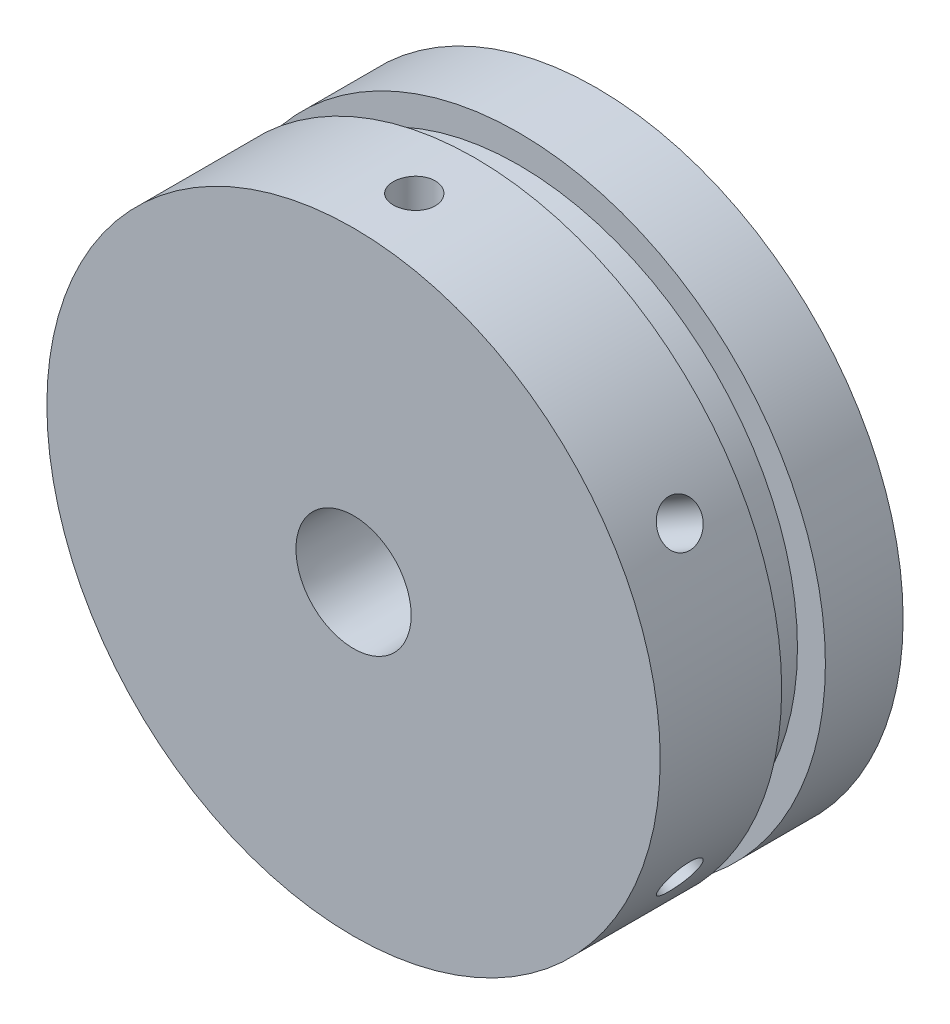
SolidWorks part; units mm, degrees
material "6061-T6 (SS)"
ref_plane "Front Plane" through (0, 0, 0) normal (0, 0, 1) x (1, 0, 0)
ref_plane "Top Plane" through (0, 0, 0) normal (0, 1, 0) x (1, 0, 0)
ref_plane "Right Plane" through (0, 0, 0) normal (1, 0, 0) x (0, 0, -1)
sketch "Sketch2" plane through (0, 0, 0) normal (0, 0, 1) x (1, 0, 0)
  circle A0 centre (0, 0) radius 25.25
  dimension "D1" = 50.5
extrude "Boss-Extrude1" add sketch "Sketch2" along normal blind 20
sketch "Sketch3" plane through (0, 0, 0) normal (1, 0, 0) x (0, 0, -1)
  line L0 (0, 25.25) -> (-20, 25.25) construction
  line L1 (-10, 25.25) -> (-6.4, 25.25)
  line L2 (-10, 25.25) -> (-10, 22.95)
  line L3 (-10, 22.95) -> (-6.4, 22.95)
  line L4 (-6.4, 25.25) -> (-6.4, 22.95)
  line L5 (0, 0) -> (-20.027, 0) construction
  dimension "D1" = 2.3
  dimension "D2" = 3.6
  dimension "D3" = 10
revolve "Cut-Revolve1" cut sketch "Sketch3" angle 360 about L5
ref_plane "Plane1" through (0, 25.25, 0) normal (0, 1, 0) x (1, 0, 0)
sketch "Sketch4" plane through (0, 25.25, 0) normal (0, 1, 0) x (1, 0, 0)
  line L0 (0, 0) -> (0, -20.5452) construction
hole_wizard "#8-32 Tapped Hole2" positions "3DSketch3" profile "Sketch7" tap size "#8-32" standard "ANSI Inch"
sketch3d "3DSketch3"
  line L0 (0, 25.25, 0) -> (0, 25.25, 20.5452) construction
  circle A1 centre (0, 0, 20) radius 25.25 construction
  point P0 (0, 25.25, 15)
  point P8 (0, 25.25, 20)
  point P12 (0, 0, 45.25)
  dimension "D1" = 5
sketch "Sketch7" plane through (0, 25.25, 15) normal (1, 0, 0) x (0, 0, 1)
  line L0 (0, 0) -> (0, 11.0378)
  line L1 (0, 11.0378) -> (1.7272, 10)
  line L2 (1.7272, 10) -> (1.7272, 0)
  line L5 (1.7272, 0) -> (0, 0)
  line L10 (0, 11.0378) -> (-1.7272, 10) construction
  line L11 (0, -6.35) -> (0, 107.95) construction
  dimension "Tap Drill Dia." = 3.4544
  dimension "Tap Drill Depth" = 10
  dimension "Drill Angle" = 118
cosmetic thread "Hole Thread5" parameters "D1"=8.33, "D2"=4.1656
sketch "Sketch9" plane through (0, 0, 0) normal (1, 0, 0) x (0, 0, -1)
  line L0 (-21.7688, 0) -> (0, 0) construction
pattern_circular "CirPattern1" count 6 over 360 about axis through (0, 0, 21.7688) along (0, 0, -1) of "#8-32 Tapped Hole2"
cosmetic thread "Hole Thread6" parameters "D1"=8.33, "D2"=4.1656
cosmetic thread "Hole Thread7" parameters "D1"=8.33, "D2"=4.1656
cosmetic thread "Hole Thread8" parameters "D1"=8.33, "D2"=4.1656
cosmetic thread "Hole Thread9" parameters "D1"=8.33, "D2"=4.1656
cosmetic thread "Hole Thread10" parameters "D1"=8.33, "D2"=4.1656
hole_wizard "1/8 NPT Tapped Hole1" positions "Sketch10" profile "Sketch11" size "1/8" standard "ANSI Inch"
sketch "Sketch10" plane through (0, 0, 20) normal (0, 0, 1) x (1, 0, 0)
  line L1 (-6.35, 0) -> (6.35, 0) construction
  point P0 (0, 0)
cosmetic thread "Hole Thread11" parameters "D1"=6.92, "D2"=10.2867
sketch "Sketch11" plane through (0, 0, 20) normal (1, 0, 0) x (0, -1, 0)
  line L0 (0, 0) -> (0, 17.5335)
  line L1 (4.2164, 15) -> (0, 17.5335)
  line L2 (-4.2164, 15) -> (0, 17.5335) construction
  line L3 (4.2164, 15) -> (4.2164, 6.92)
  line L4 (4.2164, 6.92) -> (4.5286, 6.92)
  line L5 (4.5286, 6.92) -> (4.7446, 0)
  line L6 (-4.5286, 6.92) -> (-4.7446, 0) construction
  line L7 (4.7446, 0) -> (0, 0)
  line L8 (0, -6.35) -> (0, 107.95) construction
  line L11 (-4.2164, 6.92) -> (-4.5286, 6.92) construction
  dimension "Tap Drill Dia." = 8.4328
  dimension "Tap Drill Depth" = 15
  dimension "Thread Dia." = 9.4892
  dimension "Thread Angle" = 3.576
  dimension "Thread Depth" = 6.92
  dimension "Drill Angle" = 118
